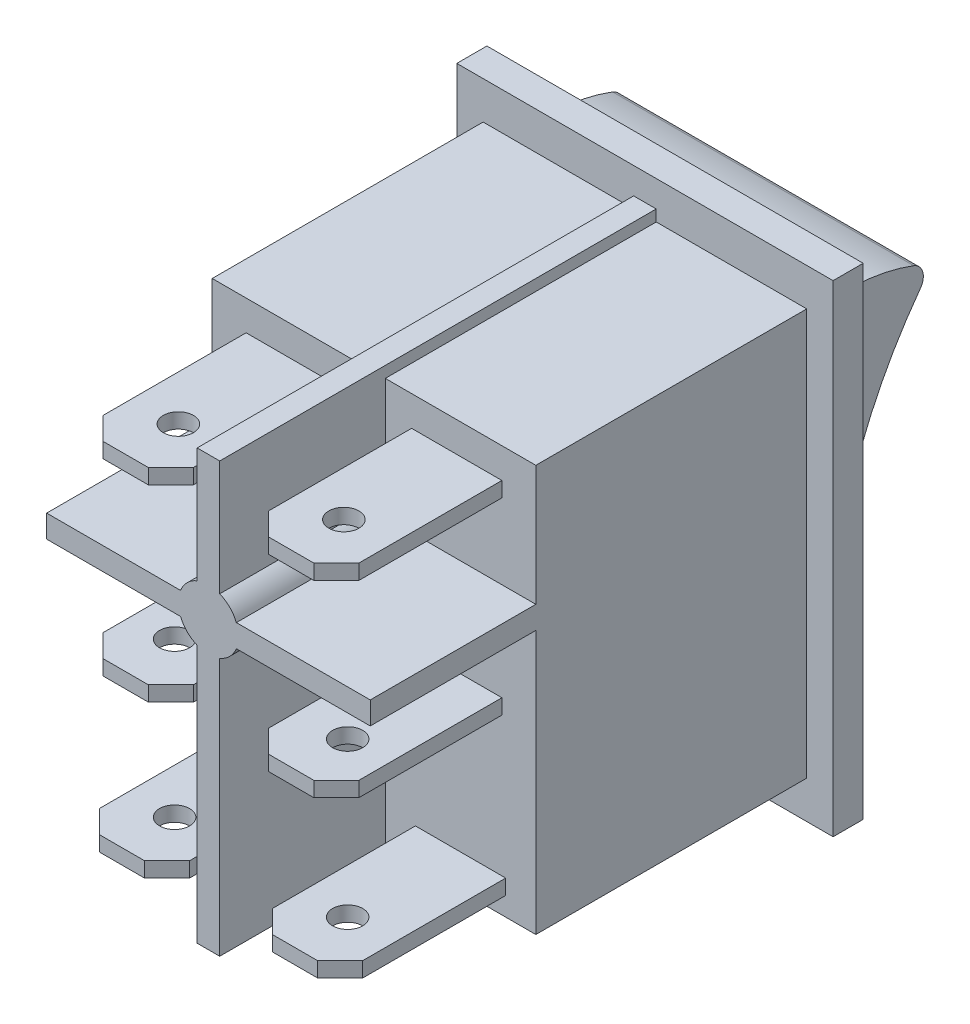
SolidWorks part; units mm, degrees
ref_plane "Спереди" through (0, 0, 0) normal (0, 0, 1) x (1, 0, 0)
ref_plane "Сверху" through (0, 0, 0) normal (0, 1, 0) x (1, 0, 0)
ref_plane "Справа" through (0, 0, 0) normal (1, 0, 0) x (0, 0, -1)
sketch "Эскиз1" plane through (0, 0, 0) normal (0, 0, 1) x (1, 0, 0)
  line L0 (0, 0) -> (25, 0)
  line L1 (25, 0) -> (25, 32)
  line L2 (25, 32) -> (0, 32)
  line L3 (0, 32) -> (0, 0)
  dimension "D1" = 32
  dimension "D2" = 25
extrude "Бобышка-Вытянуть1" add sketch "Эскиз1" along normal blind 2
sketch "Эскиз2" plane through (0, 0, 2) normal (0, 0, 1) x (1, 0, 0)
  line L0 (25, 32) -> (0, 32) construction
  line L1 (0, 0) -> (25, 0) construction
  line L2 (0, 32) -> (0, 0) construction
  line L3 (25, 0) -> (25, 32) construction
  line L8 (1.75, 29.5) -> (1.75, 2.5)
  line L9 (1.75, 2.5) -> (23.25, 2.5)
  line L10 (23.25, 2.5) -> (23.25, 29.5)
  line L11 (23.25, 29.5) -> (1.75, 29.5)
  dimension "D1" = 2.5
  dimension "D2" = 2.5
  dimension "D3" = 1.75
  dimension "D4" = 1.75
extrude "Бобышка-Вытянуть2" add sketch "Эскиз2" along normal blind 18
sketch "Эскиз3" plane through (0, 0, 2) normal (0, 0, 1) x (1, 0, 0)
  line L0 (11.75, 1.75) -> (13.25, 1.75)
  line L1 (23.25, 29.5) -> (1.75, 29.5) construction
  line L2 (11.75, 30.25) -> (13.25, 30.25)
  line L3 (13.25, 30.25) -> (13.25, 1.75)
  line L4 (23.25, 2.5) -> (23.25, 29.5) construction
  line L5 (1.75, 2.5) -> (23.25, 2.5) construction
  line L7 (11.75, 1.75) -> (11.75, 30.25)
  dimension "D1" = 0.75
  dimension "D2" = 1.5
  dimension "D3" = 10
  dimension "D4" = 0.75
extrude "Бобышка-Вытянуть3" add sketch "Эскиз3" along normal blind 29
sketch "Эскиз4" plane through (0, 0, 20) normal (0, 0, 1) x (1, 0, 0)
  line L2 (1.75, 21.5) -> (23.25, 21.5)
  line L3 (1.75, 29.5) -> (1.75, 2.5) construction
  line L4 (23.25, 2.5) -> (23.25, 29.5) construction
  line L5 (23.25, 21.5) -> (23.25, 20)
  line L7 (1.75, 20) -> (1.75, 21.5)
  line L8 (1.75, 20) -> (23.25, 20)
extrude "Бобышка-Вытянуть4" add sketch "Эскиз4" along normal up to surface (11 mm away) up to face at (12.5, 16, 31)
sketch "Эскиз6" plane through (0, 0, 31) normal (0, 0, 1) x (1, 0, 0)
  circle A0 centre (12.5, 20.75) radius 2
  dimension "D1" = 4
extrude "Бобышка-Вытянуть5" add sketch "Эскиз6" against normal up to surface (11 mm away) up to face at (18.25, 11.25, 20)
sketch "Эскиз7" plane through (0, 0, 20) normal (0, 0, 1) x (1, 0, 0)
  line L0 (4.0026, 27.5) -> (10.0026, 27.5)
  line L1 (12.5, 30.25) -> (12.5, 1.75) construction
  line L4 (10.0026, 27.5) -> (10.0026, 26.5)
  line L5 (10.0026, 26.5) -> (4.0026, 26.5)
  line L6 (4.0026, 26.5) -> (4.0026, 27.5)
  line L8 (3.75, 4.75) -> (3.75, 3.75)
  line L9 (9.75, 4.75) -> (3.75, 4.75)
  line L10 (4.0026, 15) -> (4.0026, 14)
  line L11 (10.0026, 15) -> (4.0026, 15)
  line L12 (10.0026, 14) -> (10.0026, 15)
  line L13 (4.0026, 14) -> (10.0026, 14)
  line L14 (9.75, 3.75) -> (9.75, 4.75)
  line L15 (3.75, 3.75) -> (9.75, 3.75)
  line L16 (13.25, 30.25) -> (11.75, 30.25) construction
  line L17 (11.75, 1.75) -> (13.25, 1.75) construction
  line L18 (21.25, 3.75) -> (15.25, 3.75)
  line L19 (15.25, 3.75) -> (15.25, 4.75)
  line L20 (20.9974, 14) -> (14.9974, 14)
  line L21 (14.9974, 14) -> (14.9974, 15)
  line L22 (14.9974, 15) -> (20.9974, 15)
  line L23 (20.9974, 15) -> (20.9974, 14)
  line L24 (15.25, 4.75) -> (21.25, 4.75)
  line L25 (21.25, 4.75) -> (21.25, 3.75)
  line L26 (20.9974, 26.5) -> (20.9974, 27.5)
  line L27 (14.9974, 26.5) -> (20.9974, 26.5)
  line L28 (14.9974, 27.5) -> (14.9974, 26.5)
  line L29 (20.9974, 27.5) -> (14.9974, 27.5)
extrude "Бобышка-Вытянуть6" add sketch "Эскиз7" along normal up to surface (11 mm away) up to face at (12.5, 19.5625, 31)
sketch "Эскиз8" plane through (0, 3.75, 0) normal (0, -1, 0) x (1, 0, 0)
  circle A0 centre (6.75, 27.5) radius 1
  circle A1 centre (18.25, 27.5) radius 1
  dimension "D1" = 2
  dimension "D2" = 2
extrude "Вырез-Вытянуть1" cut sketch "Эскиз8" against normal blind 15
sketch "Эскиз9" plane through (0, 27.5, 0) normal (0, 1, 0) x (1, 0, 0)
  circle A0 centre (17.9974, -27.5) radius 1
  circle A1 centre (7.0026, -27.5) radius 1
  dimension "D1" = 2
  dimension "D2" = 2
extrude "Вырез-Вытянуть2" cut sketch "Эскиз9" against normal blind 5
chamfer "Фаска1" distance 1.5 angle 45 12 edges at (9.75, 4.25, 31) (3.75, 4.25, 31) (15.25, 4.25, 31) (21.25, 4.25, 31) (10.0026, 14.5, 31) (4.0026, 14.5, 31) (14.9974, 14.5, 31) (20.9974, 14.5, 31) (14.9974, 27, 31) (20.9974, 27, 31) (10.0026, 27, 31) (4.0026, 27, 31)
sketch "Эскиз10" plane through (0, 0, 0) normal (0, 0, -1) x (-1, 0, 0)
  line L8 (-22.5, 28.5) -> (-22.5, 3.5)
  line L9 (-22.5, 3.5) -> (-2.5, 3.5)
  line L10 (-2.5, 3.5) -> (-2.5, 28.5)
  line L11 (-2.5, 28.5) -> (-22.5, 28.5)
extrude "Вырез-Вытянуть3" cut sketch "Эскиз10" against normal blind 5
sketch "Эскиз12" plane through (22.5, 0, 0) normal (-1, 0, 0) x (0, 0, 1)
  line L1 (5, 3.5) -> (5, 28.5) construction
  line L3 (5, 5.2659) -> (5, 26.7341)
  arc A0 (0.5838, 3.6593) -> (5, 5.2659) centre (-1.4054, 16) ccw
  arc A1 (-0.569, 4.7595) -> (-6.3013, 26.1528) centre (-30.6064, 8.1756) ccw
  arc A2 (-0.569, 4.7595) -> (0.5838, 3.6593) centre (0.4246, 4.6465) ccw
  arc A3 (-6.3013, 26.1528) -> (-5.8531, 27.682) centre (-5.4973, 26.7474) cw
  arc A4 (5, 26.7341) -> (-5.8531, 27.682) centre (-1.4054, 16) ccw
extrude "Бобышка-Вытянуть7" add sketch "Эскиз12" along normal up to surface (20 mm away) up to face at (2.5, 16, 2.5)
